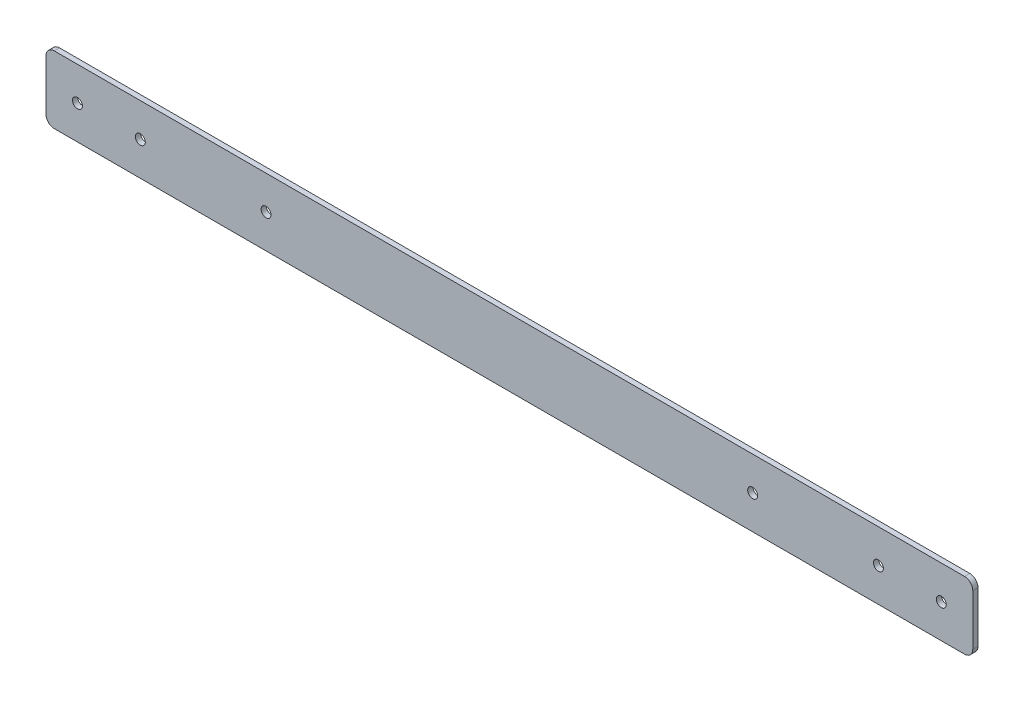
SolidWorks part; units mm, degrees
material "Malleable Cast Iron"
ref_plane "Front" through (0, 0, 0) normal (0, 0, 1) x (1, 0, 0)
ref_plane "Top" through (0, 0, 0) normal (0, 1, 0) x (1, 0, 0)
ref_plane "Right" through (0, 0, 0) normal (1, 0, 0) x (0, 0, -1)
sketch "Sketch1" plane through (0, 0, 0) normal (0, 0, 1) x (1, 0, 0)
  line L0 (0, 40.8) -> (1123, 40.8) construction
  line L1 (10, 0) -> (1113, 0)
  line L2 (0, 10) -> (0, 71.6)
  line L3 (10, 81.6) -> (1113, 81.6)
  line L4 (1123, 10) -> (1123, 71.6)
  line L5 (561.5, 81.6) -> (561.5, 0) construction
  arc A0 (1113, 81.6) -> (1123, 71.6) centre (1113, 71.6) cw
  arc A1 (1113, 0) -> (1123, 10) centre (1113, 10) ccw
  arc A2 (10, 0) -> (0, 10) centre (10, 10) cw
  arc A3 (0, 71.6) -> (10, 81.6) centre (10, 71.6) cw
  circle A4 centre (38.1, 40.8) radius 6
  circle A5 centre (114.3, 40.8) radius 6
  circle A6 centre (266.7, 40.8) radius 6
  circle A7 centre (856.3, 40.8) radius 6
  circle A8 centre (1008.7, 40.8) radius 6
  circle A9 centre (1084.9, 40.8) radius 6
  point P9 (1123, 0)
  point P12 (0, 0)
  point P15 (0, 81.6)
  dimension "D3" = 10
  dimension "D4" = 12
  dimension "D5" = 38.1
  dimension "D1" = 1123
  dimension "D2" = 81.6
  dimension "D6" = 114.3
  dimension "D7" = 266.7
extrude "Boss-Extrude1" add sketch "Sketch1" along normal blind 6.35
